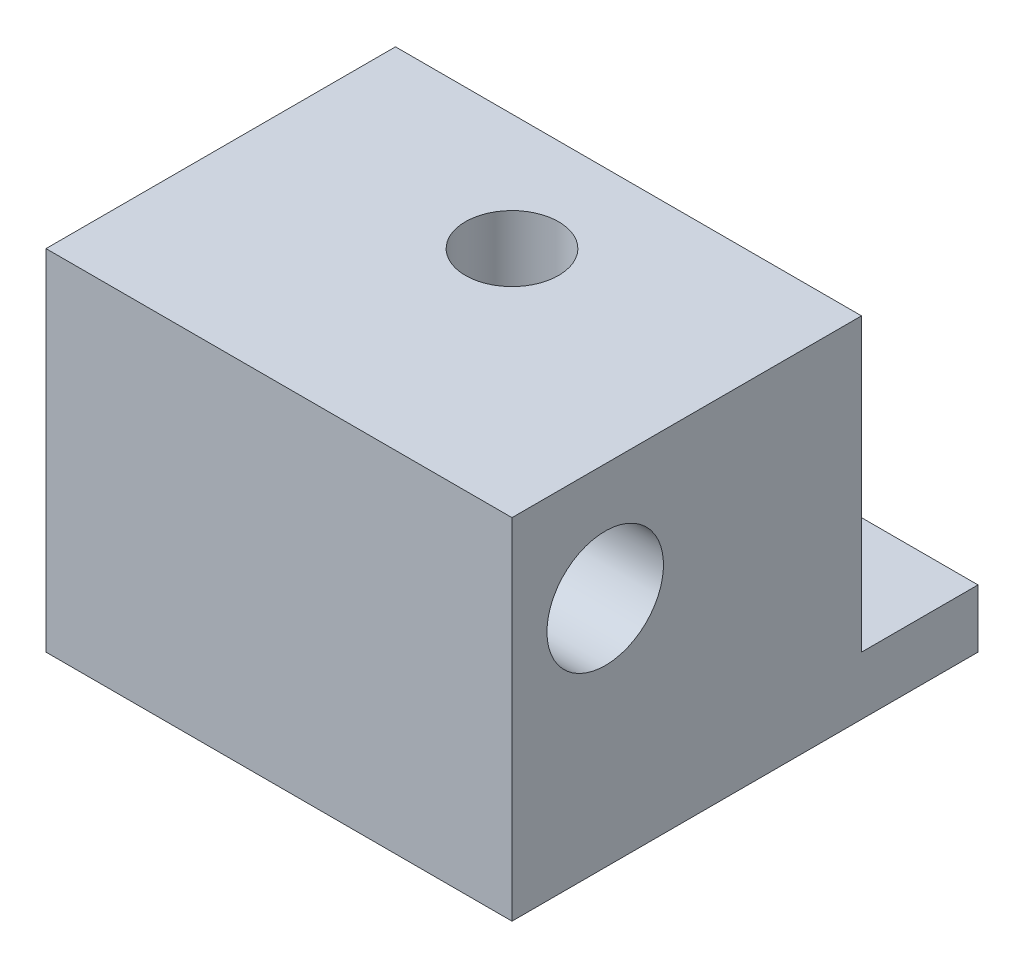
SolidWorks part; units mm, degrees
ref_plane "Front Plane" through (0, 0, 0) normal (0, 0, 1) x (1, 0, 0)
ref_plane "Top Plane" through (0, 0, 0) normal (0, 1, 0) x (1, 0, 0)
ref_plane "Right Plane" through (0, 0, 0) normal (1, 0, 0) x (0, 0, -1)
sketch "Sketch1" plane through (0, 0, 0) normal (0, 1, 0) x (1, 0, 0)
  line L1 (-20, -20) -> (20, -20)
  line L2 (-20, -20) -> (-20, 20)
  line L3 (-20, 20) -> (20, 20)
  line L4 (20, -20) -> (20, 20)
  line L5 (-20, -20) -> (20, 20) construction
  line L6 (-20, 20) -> (20, -20) construction
  point P0 (0, 0)
  dimension "D1" = 40
extrude "Boss-Extrude1" add sketch "Sketch1" along normal blind 30
sketch "Sketch2" plane through (0, 30, 0) normal (0, 1, 0) x (1, 0, 0)
  circle A0 centre (0, 0) radius 4
  dimension "D1" = 8
extrude "Cut-Extrude1" cut sketch "Sketch2" against normal through all
sketch "Sketch3" plane through (-20, 0, 0) normal (-1, 0, 0) x (0, 0, 1)
  line L0 (-20, 0) -> (20, 0) construction
  circle A0 centre (12, 20) radius 5
  dimension "D1" = 10
  dimension "D2" = 20
  dimension "D3" = 12
extrude "Cut-Extrude2" cut sketch "Sketch3" against normal through all both and the other way through all contours A0
sketch "Sketch4" plane through (-20, 0, 0) normal (-1, 0, 0) x (0, 0, 1)
  line L0 (-20, 0) -> (20, 0) construction
  line L1 (-20, 30) -> (-10, 30)
  line L2 (-20, 30) -> (-20, 5)
  line L3 (-20, 5) -> (-10, 5)
  line L4 (-10, 30) -> (-10, 5)
  dimension "D1" = 10
  dimension "D2" = 5
extrude "Cut-Extrude3" cut sketch "Sketch4" against normal through all
